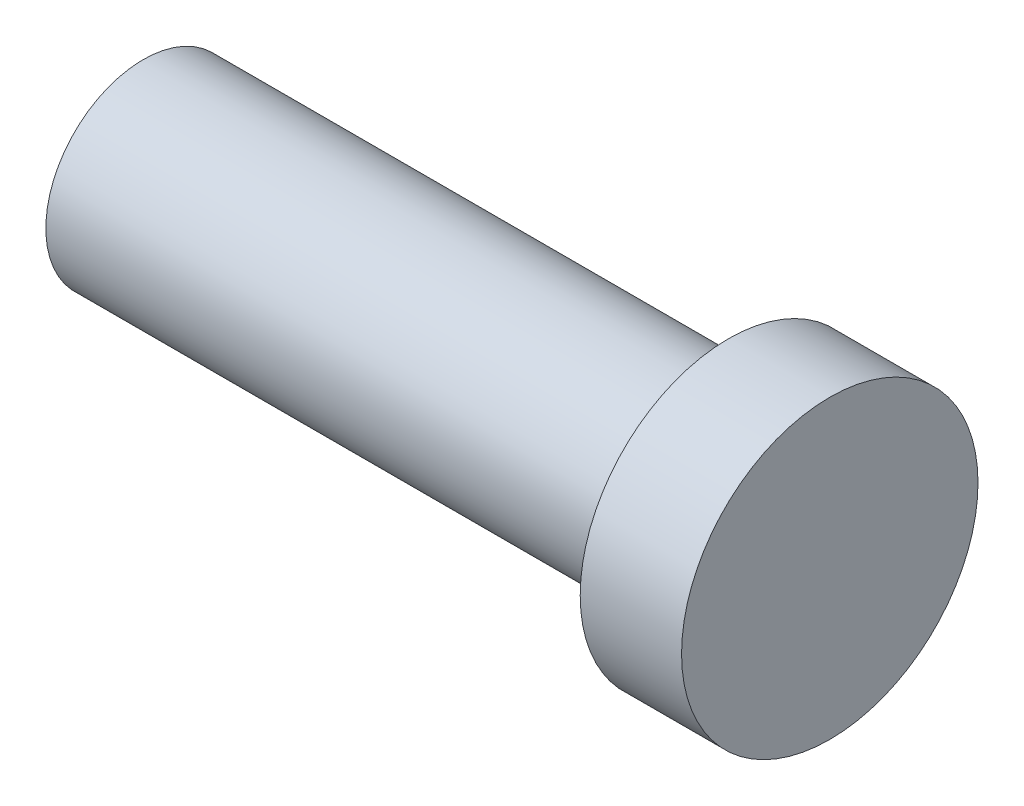
SolidWorks part; units mm, degrees
ref_plane "Front Plane" through (0, 0, 0) normal (0, 0, 1) x (1, 0, 0)
ref_plane "Top Plane" through (0, 0, 0) normal (0, 1, 0) x (1, 0, 0)
ref_plane "Right Plane" through (0, 0, 0) normal (1, 0, 0) x (0, 0, -1)
sketch "Sketch1" plane through (0, 0, 0) normal (1, 0, 0) x (0, 0, -1)
  circle A0 centre (0, 0) radius 4.826
  dimension "D1" = 9.652
extrude "Boss-Extrude1" add sketch "Sketch1" against normal blind 3.3
sketch "Sketch2" plane through (-3.3, 0, 0) normal (-1, 0, 0) x (0, 0, 1)
  circle A0 centre (0, 0) radius 3.175
  dimension "D1" = 6.35
extrude "Boss-Extrude2" add sketch "Sketch2" along normal blind 19.05
